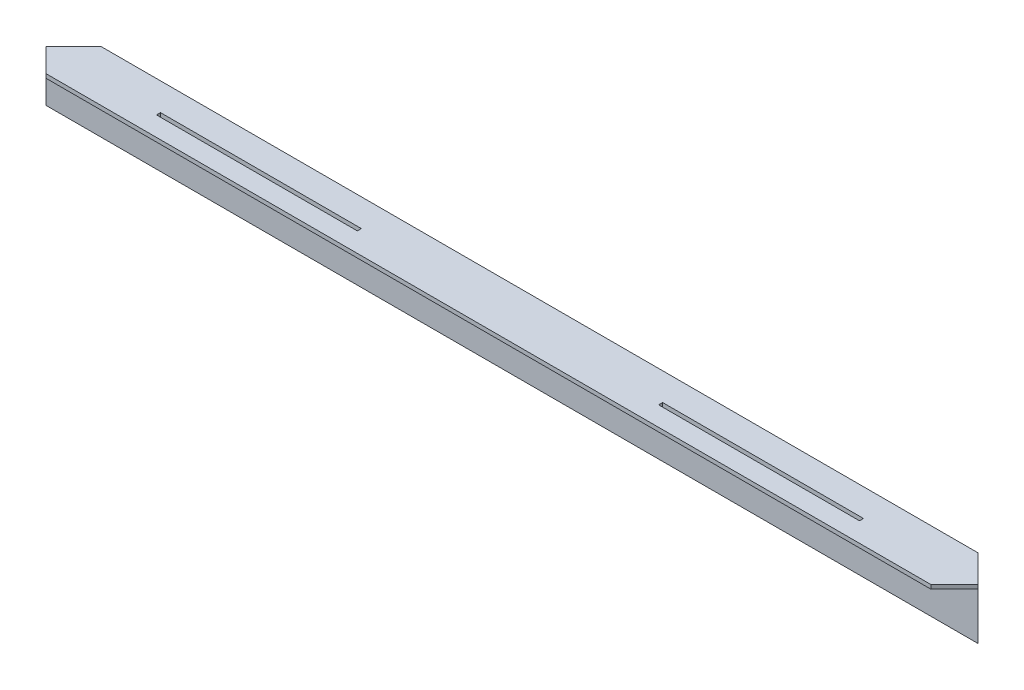
SolidWorks part; units mm, degrees
ref_plane "Plano frontal" through (0, 0, 0) normal (0, 0, 1) x (1, 0, 0)
ref_plane "Plano superior" through (0, 0, 0) normal (0, 1, 0) x (1, 0, 0)
ref_plane "Plano direito" through (0, 0, 0) normal (1, 0, 0) x (0, 0, -1)
sketch "Esboço1" plane through (0, 0, 0) normal (1, 0, 0) x (0, 0, -1)
  line L6 (-193.7, 0) -> (-168.3, 0)
  line L8 (-182, -25.4) -> (-180, -25.4)
  line L12 (-193.7, 0) -> (-193.7, -2)
  line L13 (-193.7, -2) -> (-182, -2)
  line L14 (-181, -28.6659) -> (-181, 4.0081) construction
  line L15 (-182, -2) -> (-182, -25.4)
  line L16 (-168.3, 0) -> (-168.3, -2)
  line L17 (-180, -2) -> (-180, -25.4)
  line L18 (-168.3, -2) -> (-180, -2)
  dimension "D1" = 2
  dimension "D2" = 25.4
  dimension "D3" = 180
  dimension "D4" = 25.4
extrude "Ressalto-extrusão1" add sketch "Esboço1" along normal mid plane 464
sketch "Esboço2" plane through (0, 0, 0) normal (0, 1, 0) x (1, 0, 0)
  line L0 (-232, -182) -> (-218.3, -168.3)
  line L2 (-218.3, -168.3) -> (-232, -168.3)
  line L3 (-232, -168.3) -> (-232, -182)
  line L4 (232, -182) -> (218.3, -168.3)
  line L5 (218.3, -168.3) -> (232, -168.3)
  line L6 (232, -168.3) -> (232, -182)
  line L7 (232, -168.3) -> (-232, -168.3) construction
extrude "Corte-extrusão1" cut sketch "Esboço2" against normal mid plane 100
sketch "Esboço3" plane through (0, 0, 0) normal (0, 1, 0) x (1, 0, 0)
  line L0 (0, -128.3028) -> (0, -226.5437) construction
  line L1 (-175, -182) -> (-175, -184)
  line L2 (232, -182) -> (-232, -182) construction
  line L3 (-175, -184) -> (-75, -184)
  line L4 (-125, -151.8666) -> (-125, -209.244) construction
  line L5 (-75, -182) -> (-75, -184)
  line L6 (-75, -182) -> (-175, -182)
  line L7 (125, -151.8666) -> (125, -209.244) construction
  line L8 (75, -182) -> (175, -182)
  line L9 (75, -182) -> (75, -184)
  line L10 (175, -184) -> (75, -184)
  line L11 (175, -182) -> (175, -184)
  dimension "D1" = 250
  dimension "D2" = 100
  dimension "D3" = 2
extrude "Corte-extrusão2" cut sketch "Esboço3" against normal through all
sketch "Esboço4" plane through (0, 0, 0) normal (0, 1, 0) x (1, 0, 0)
  line L0 (-232, -182) -> (-220.3, -193.7)
  line L1 (232, -193.7) -> (-232, -193.7) construction
  line L2 (-220.3, -193.7) -> (-232, -193.7)
  line L3 (-232, -182) -> (-232, -193.7) construction
  line L4 (-232, -193.7) -> (-232, -182)
  line L5 (232, -182) -> (220.3, -193.7)
  line L6 (232, -182) -> (218.3, -168.3) construction
  line L7 (220.3, -193.7) -> (232, -193.7)
  line L8 (232, -193.7) -> (232, -182)
extrude "Corte-extrusão3" cut sketch "Esboço4" against normal mid plane 100
